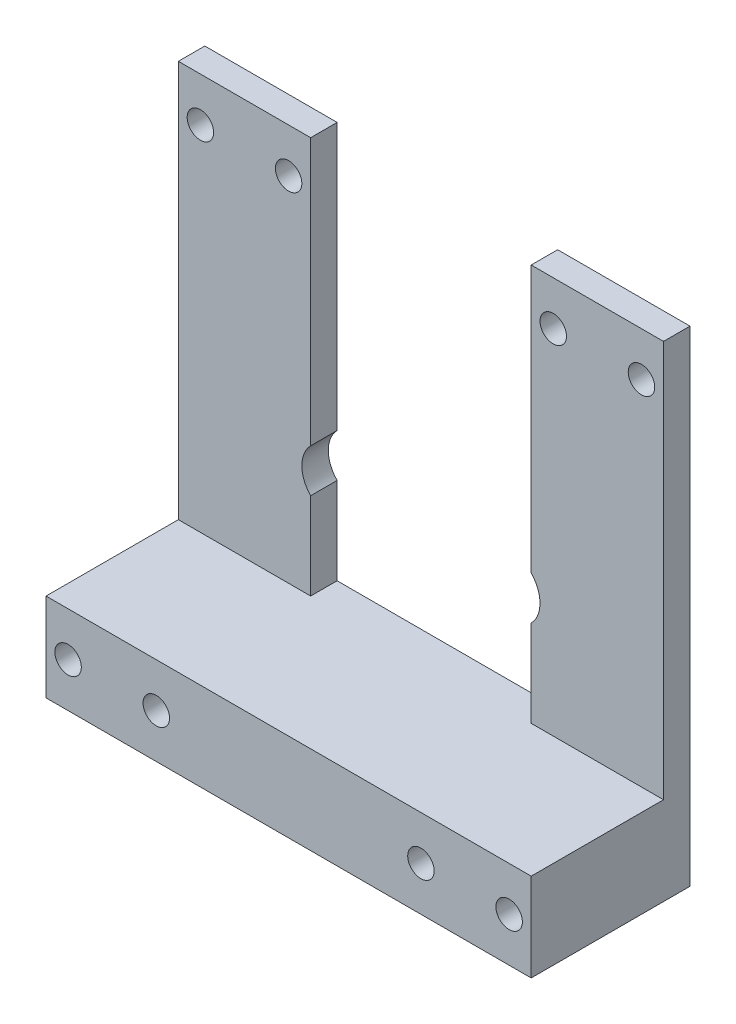
SolidWorks part; units mm, degrees
ref_plane "Front Plane" through (0, 0, 0) normal (0, 0, 1) x (1, 0, 0)
ref_plane "Top Plane" through (0, 0, 0) normal (0, 1, 0) x (1, 0, 0)
ref_plane "Right Plane" through (0, 0, 0) normal (1, 0, 0) x (0, 0, -1)
sketch "Sketch1" plane through (0, 0, 0) normal (0, 0, 1) x (1, 0, 0)
  line L1 (0, 0) -> (-55, 0)
  line L2 (0, 0) -> (0, 10)
  line L3 (0, 10) -> (-55, 10)
  line L4 (-55, 0) -> (-55, 10)
  circle A4 centre (-2.5, 5) radius 1.5
  circle A5 centre (-12.5, 5) radius 1.5
  circle A6 centre (-42.5, 5) radius 1.5
  circle A7 centre (-52.5, 5) radius 1.5
extrude "Boss-Extrude1" add sketch "Sketch1" along normal blind 15
sketch "Sketch2" plane through (0, 0, 0) normal (0, 0, -1) x (-1, 0, 0)
  line L0 (55, 10) -> (55, 0) construction
  line L1 (0, 0) -> (15, 0)
  line L2 (0, 0) -> (0, 55)
  line L3 (0, 55) -> (15, 55)
  line L4 (15, 0) -> (15, 55)
  line L5 (55, 0) -> (40, 0)
  line L6 (55, 0) -> (55, 55)
  line L7 (55, 55) -> (40, 55)
  line L8 (40, 0) -> (40, 55)
  line L9 (15, 0) -> (40, 0)
  line L10 (0, 10) -> (55, 10) construction
  line L11 (0, 10) -> (55, 10)
  circle A0 centre (12.5, 50) radius 1.5 construction
  circle A1 centre (2.5, 50) radius 1.5 construction
  circle A2 centre (2.5, 5) radius 1.5 construction
  circle A3 centre (12.5, 5) radius 1.5 construction
  circle A4 centre (52.5, 5) radius 1.5 construction
  circle A5 centre (42.5, 5) radius 1.5 construction
  circle A6 centre (52.5, 50) radius 1.5 construction
  circle A7 centre (42.5, 50) radius 1.5 construction
  circle A8 centre (12.5, 50) radius 1.5
  circle A9 centre (2.5, 50) radius 1.5
  circle A10 centre (2.5, 5) radius 1.5
  circle A11 centre (12.5, 5) radius 1.5
  circle A12 centre (52.5, 5) radius 1.5
  circle A13 centre (42.5, 5) radius 1.5
  circle A14 centre (52.5, 50) radius 1.5
  circle A15 centre (42.5, 50) radius 1.5
  circle A16 centre (17.5, 22.3) radius 3.5
  circle A17 centre (37.5, 22.3) radius 3.5
  line M9 (0, 10) -> (0, 0)
  line M10 (0, 0) -> (55, 0)
  line M11 (55, 0) -> (55, 10)
  line M12 (55, 10) -> (0, 10)
  circle M13 centre (2.5, 5) radius 1.5
  circle M14 centre (12.5, 5) radius 1.5
  circle M15 centre (42.5, 5) radius 1.5
  circle M16 centre (52.5, 5) radius 1.5
extrude "Boss-Extrude2" add sketch "Sketch2" along normal blind 3 contours L8 L4 M10 M12 | A16 L4 L3 L2 A9 A8 M12 | L4 M10 M12 M9 M14 M13 | L8 M10 M11 M12 M15 M16 | A17 L8 L6 L7 A15 A14 M12
